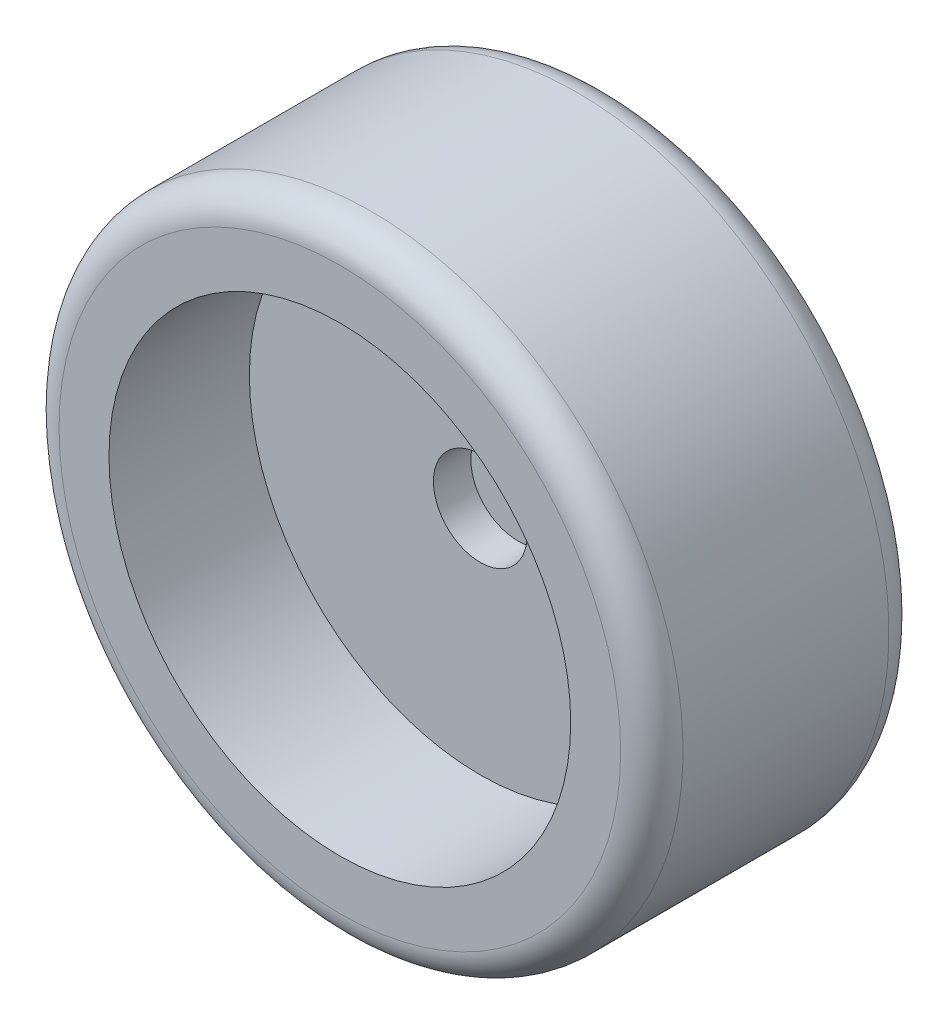
SolidWorks part; units mm, degrees
material "Material"
ref_plane "Front Plane" through (0, 0, 0) normal (0, 0, 1) x (1, 0, 0)
ref_plane "Top Plane" through (0, 0, 0) normal (0, 1, 0) x (1, 0, 0)
ref_plane "Right Plane" through (0, 0, 0) normal (1, 0, 0) x (0, 0, -1)
ref_plane "Plane1" through (0, 0, 0) normal (0, -1, 0) x (1, 0, 0)
sketch "Sketch1" plane through (0, 0, 0) normal (0, -1, 0) x (1, 0, 0)
  line L0 (7.5, 14.5) -> (0, 14.5)
  line L1 (0, 14.5) -> (0, 0)
  line L2 (0, 0) -> (45, 0)
  line L3 (50, 5) -> (50, 38)
  line L4 (45, 43) -> (37, 43)
  line L5 (37, 43) -> (37, 20.5)
  line L6 (37, 20.5) -> (7.5, 20.5)
  line L7 (7.5, 20.5) -> (7.5, 14.5)
  line L8 (0, 43) -> (0, 0) construction
  arc A0 (45, 0) -> (50, 5) centre (45, 5) ccw
  arc A1 (50, 38) -> (45, 43) centre (45, 38) ccw
revolve "Revolve1" add sketch "Sketch1" angle 360 about L8
